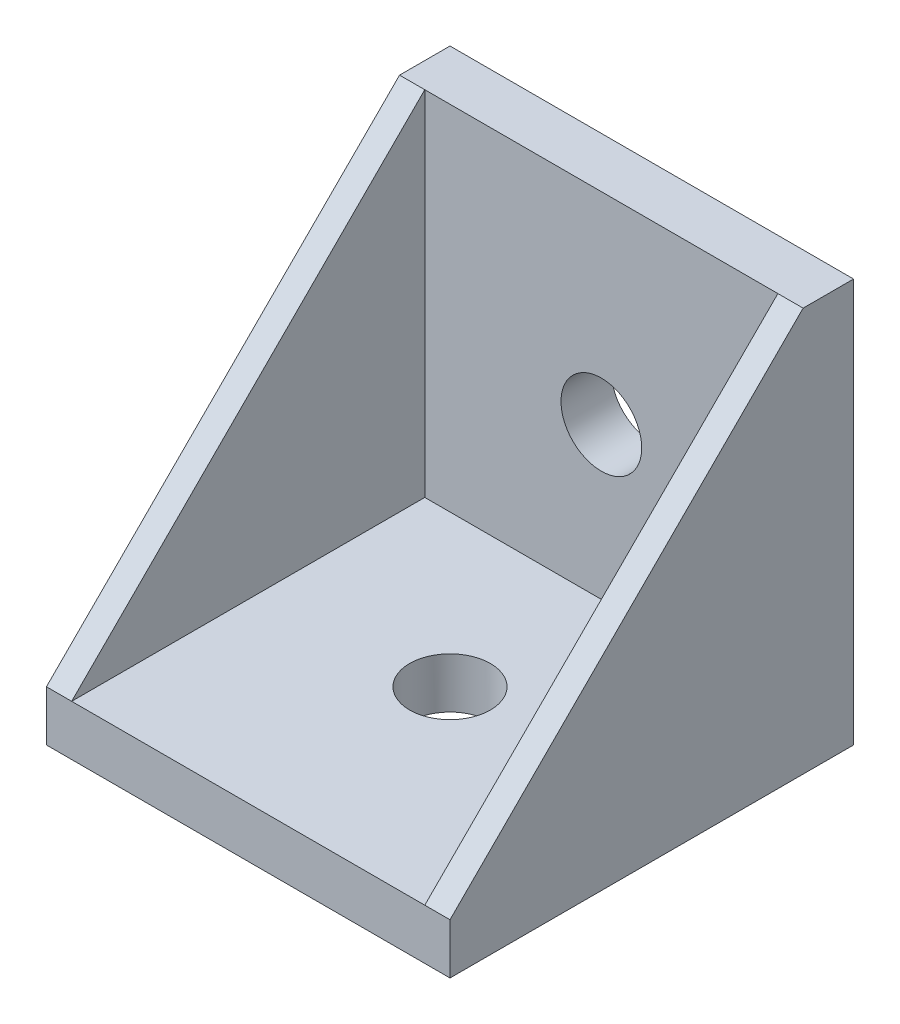
SolidWorks part; units mm, degrees
material "Alloy Steel"
ref_plane "Front Plane" through (0, 0, 0) normal (0, 0, 1) x (1, 0, 0)
ref_plane "Top Plane" through (0, 0, 0) normal (0, 1, 0) x (1, 0, 0)
ref_plane "Right Plane" through (0, 0, 0) normal (1, 0, 0) x (0, 0, -1)
sketch "Sketch1" plane through (0, 0, 0) normal (0, 1, 0) x (1, 0, 0)
  line L1 (-20, 20) -> (20, 20)
  line L2 (-20, 20) -> (-20, -20)
  line L3 (-20, -20) -> (20, -20)
  line L4 (20, 20) -> (20, -20)
  line L5 (-20, 20) -> (20, -20) construction
  line L6 (-20, -20) -> (20, 20) construction
  point P0 (0, 0)
  dimension "D1" = 40
  dimension "D2" = 40
extrude "Boss-Extrude1" add sketch "Sketch1" along normal blind 40
sketch "Sketch2" plane through (20, 0, 0) normal (1, 0, 0) x (0, 0, -1)
  line L0 (15, 40) -> (-20, 5)
  line L1 (-20, 40) -> (20, 40) construction
  line L2 (-20, 40) -> (-20, 0) construction
  line L3 (-20, 5) -> (-20, 40)
  line L4 (-20, 40) -> (15, 40)
  line L5 (20, 40) -> (20, 0) construction
  dimension "D1" = 5
  dimension "D2" = 5
extrude "Cut-Extrude1" cut sketch "Sketch2" against normal through all both and the other way through all
sketch "Sketch4" plane through (0, 0, 20) normal (0, 0, 1) x (1, 0, 0)
  line L0 (-20, 5) -> (20, 5) construction
  line L1 (-17.5, 5) -> (17.5, 5)
  line L2 (-17.5, 5) -> (-17.5, 40)
  line L3 (-17.5, 40) -> (17.5, 40)
  line L4 (17.5, 5) -> (17.5, 40)
  line L5 (-20, 40) -> (20, 40) construction
  line L6 (20, 40) -> (20, 5) construction
  line L7 (-20, 5) -> (-20, 40) construction
  dimension "D1" = 2.5
  dimension "D2" = 2.5
extrude "Cut-Extrude2" cut sketch "Sketch4" against normal offset from surface 5 and the other way through all up to face at (0, 20, -20)
sketch "Sketch5" plane through (0, 5, 0) normal (0, 1, 0) x (1, 0, 0)
  line L0 (20, 20) -> (-20, 20) construction
  circle A0 centre (0, 0) radius 4
  dimension "D1" = 8
  dimension "D2" = 20
sketch "Sketch6" plane through (0, 0, -15) normal (0, 0, 1) x (1, 0, 0)
  line L1 (-20, 0) -> (20, 0) construction
  circle A0 centre (0, 20) radius 4
  point P2 (-20, 20)
  dimension "D1" = 8
  dimension "D2" = 20
extrude "Cut-Extrude3" cut sketch "Sketch6" against normal through all both and the other way through all
extrude "Cut-Extrude4" cut sketch "Sketch5" against normal through all both and the other way through all contours A0
